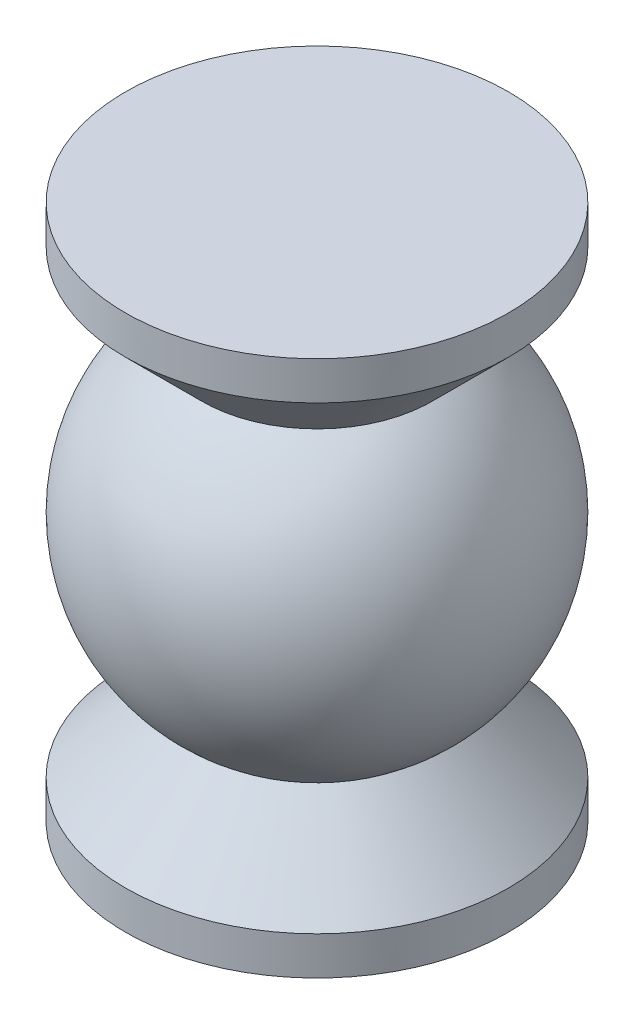
SolidWorks part; units mm, degrees
ref_plane "前视基准面" through (0, 0, 0) normal (0, 0, 1) x (1, 0, 0)
ref_plane "上视基准面" through (0, 0, 0) normal (0, 1, 0) x (1, 0, 0)
ref_plane "右视基准面" through (0, 0, 0) normal (1, 0, 0) x (0, 0, -1)
other "Configuration Table"
sketch "草图1" plane through (0, 0, 0) normal (0, 0, 1) x (1, 0, 0)
  line L0 (0, -20) -> (0, 20)
  line L1 (-15, 20) -> (15, 20)
  line L2 (-15, -20) -> (15, -20)
  line L3 (0, 20) -> (0, 35)
  line L4 (-25, 35) -> (25, 35)
  line L5 (25, 35) -> (25, 30)
  line L6 (25, 30) -> (-25, 30)
  line L7 (-25, 30) -> (-25, 35)
  line L8 (25, 30) -> (15, 20)
  line L9 (-15, 20) -> (-25, 30)
  arc A0 (-15, 20) -> (-15, -20) centre (0, 0) ccw
  arc A1 (15, -20) -> (15, 20) centre (0, 0) ccw
  point P6 (0, 0)
  point P9 (0, 20)
  point P12 (0, -20)
  point P15 (0, 35)
  dimension "D1" = 40
  dimension "D2" = 50
  dimension "D3" = 15
  dimension "D4" = 50
  dimension "D5" = 5
revolve "旋转1" add sketch "草图1" angle 360 about L0
mirror "镜向1" about plane through (0, 0, 0) normal (0, 1, 0) of "旋转1"
